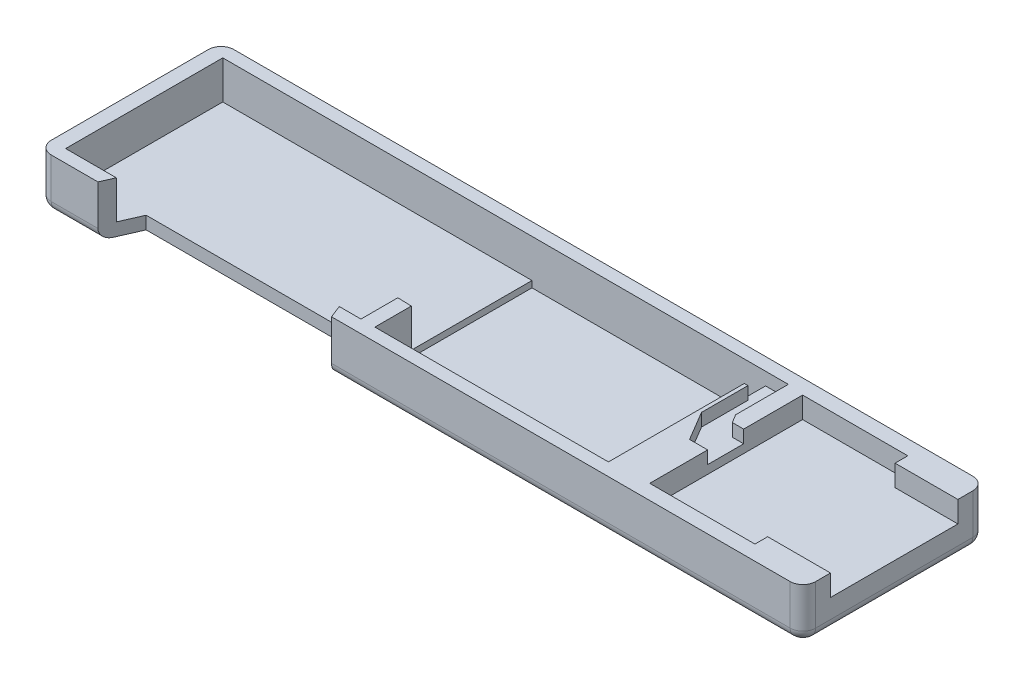
SolidWorks part; units mm, degrees
ref_plane "前视基准面" through (0, 0, 0) normal (0, 0, 1) x (1, 0, 0)
ref_plane "上视基准面" through (0, 0, 0) normal (0, 1, 0) x (1, 0, 0)
ref_plane "右视基准面" through (0, 0, 0) normal (1, 0, 0) x (0, 0, -1)
sketch "草图3" plane through (0, 0, 0) normal (0, 1, 0) x (1, 0, 0)
  line L1 (-39.9314, 29.2531) -> (140.0686, 29.2531)
  line L2 (-39.9314, 29.2531) -> (-39.9314, -13.7469)
  line L3 (-39.9314, -13.7469) -> (140.0686, -13.7469)
  line L4 (140.0686, 29.2531) -> (140.0686, -13.7469)
extrude "凸台-拉伸1" add sketch "草图3" along normal blind 12
sketch "草图4" plane through (0, 0, 0) normal (0, 1, 0) x (1, 0, 0)
  line L0 (-22.4696, -5.8589) -> (26.0023, -5.8589)
  line L1 (-39.9314, -13.7469) -> (140.0686, -13.7469) construction
  line L2 (-25.9314, -13.7469) -> (29.0686, -13.7469)
  line L5 (-25.9314, -13.7469) -> (-22.4696, -5.8589)
  line L6 (29.0686, -13.7469) -> (26.0023, -5.8589)
  point P11 (-22.4696, -5.8589)
  point P12 (26.0023, -5.8589)
extrude "切除-拉伸1" cut sketch "草图4" along normal blind 52
sketch "草图5" plane through (0, 12, 0) normal (0, 1, 0) x (1, 0, 0)
  line L6 (140.0686, -13.7469) -> (140.0686, 29.2531) construction
  line L7 (140.0686, 7.7531) -> (140.0686, 22.7531)
  line L8 (140.0686, 7.7531) -> (140.0686, -7.2469)
  line L9 (140.0686, 22.7531) -> (125.2765, 22.7531)
  line L10 (125.2765, 22.7531) -> (125.2765, -7.2469)
  line L11 (125.2765, -7.2469) -> (140.0686, -7.2469)
  point P0 (140.0686, 7.7531)
extrude "切除-拉伸2" cut sketch "草图5" against normal blind 5
sketch "草图7" plane through (0, 12, 0) normal (0, 1, 0) x (1, 0, 0)
  line L0 (125.2765, 22.7531) -> (125.2765, -7.2469) construction
  line L1 (125.2765, 7.7531) -> (125.2765, 25.7531)
  line L2 (125.2765, 7.7531) -> (125.2765, -10.2469)
  line L3 (125.2765, -10.2469) -> (100.5008, -10.2469)
  line L4 (100.5008, -10.2469) -> (100.5008, 25.7531)
  line L5 (100.5008, 25.7531) -> (125.2765, 25.7531)
  point P0 (125.2765, 7.7531)
extrude "切除-拉伸3" cut sketch "草图7" against normal blind 5
sketch "草图8" plane through (0, 12, 0) normal (0, 1, 0) x (1, 0, 0)
  line L1 (36.2763, 26.2531) -> (91.2763, 26.2531)
  line L2 (36.2763, 26.2531) -> (36.2763, -10.7469)
  line L3 (36.2763, -10.7469) -> (91.2763, -10.7469)
  line L4 (91.2763, 26.2531) -> (91.2763, -10.7469)
  line L6 (140.0686, 29.2531) -> (-39.9314, 29.2531) construction
  line L7 (29.0686, -13.7469) -> (140.0686, -13.7469) construction
  dimension "D1" = 3
  dimension "D2" = 3
extrude "切除-拉伸4" cut sketch "草图8" against normal blind 10.5
sketch "草图9" plane through (0, 12, 0) normal (0, 1, 0) x (1, 0, 0)
  line L0 (91.2763, -10.7469) -> (91.2763, 26.2531) construction
  line L1 (91.2763, 26.2531) -> (96.6358, 26.2531)
  line L2 (91.2763, 26.2531) -> (91.2763, 21.2551)
  line L4 (96.6358, 26.2531) -> (96.6358, 22.1306)
  line L5 (100.5008, 25.7531) -> (100.5008, -10.2469) construction
  line L7 (92.1327, 21.2551) -> (92.1327, 10.3104)
  line L12 (96.2367, 3.394) -> (100.5008, 3.394)
  line L13 (100.5008, 11.8772) -> (100.5008, 3.394)
  line L14 (92.1327, 10.3104) -> (96.2367, 3.394)
  line L15 (96.6358, 13.8621) -> (97.8136, 11.8772)
  line L17 (97.8136, 11.8772) -> (100.5008, 11.8772)
  line L19 (96.6358, 13.8621) -> (96.6358, 22.1306)
  line L20 (92.1327, 21.2551) -> (91.2763, 21.2551)
extrude "切除-拉伸5" cut sketch "草图9" against normal blind 3
sketch "草图10" plane through (0, 12, 0) normal (0, 1, 0) x (1, 0, 0)
  line L4 (-29.1302, -10.7469) -> (32.9986, -10.7469)
  line L5 (-29.1302, -10.7469) -> (-29.1302, -2.0631)
  line L6 (-29.1302, -2.0631) -> (32.9986, -2.0631)
  line L7 (32.9986, -10.7469) -> (32.9986, -2.0631)
extrude "切除-拉伸6" cut sketch "草图10" against normal blind 8
sketch "草图11" plane through (0, 12, 0) normal (0, 1, 0) x (1, 0, 0)
  line L0 (32.9986, -10.7469) -> (-36.5397, -10.7469)
  line L1 (36.2763, 26.2531) -> (36.2763, -10.7469) construction
  line L5 (-36.5397, 26.2531) -> (-36.5397, -10.7469)
  line L9 (36.2763, 26.2531) -> (36.2763, -2.1672)
  line L10 (-36.5397, 26.2531) -> (36.2763, 26.2531)
  line L11 (32.9986, -10.7469) -> (32.9986, -2.0631)
  line L12 (32.9986, -10.7469) -> (32.9986, -2.0631) construction
  line L13 (32.9986, -2.0631) -> (36.2763, -2.1672)
extrude "切除-拉伸8" cut sketch "草图11" against normal blind 9
fillet "圆角3" radius 3 4 edges at (140.0686, 6, -29.2531) (140.0686, 6, 13.7469) (-39.9314, 6, 13.7469) (-39.9314, 6, -29.2531)
fillet "圆角4" radius 2.5 9 edges at (50.0686, 0, -29.2531) (-39.0527, 0, 12.8682) (-31.4314, 0, 13.7469) (83.0686, 0, 13.7469) (139.1899, 0, 12.8682) (140.0686, 0, -7.7531) (139.1899, 0, -28.3744) (-39.0527, 0, -28.3744) (-39.9314, 0, -7.7531)
